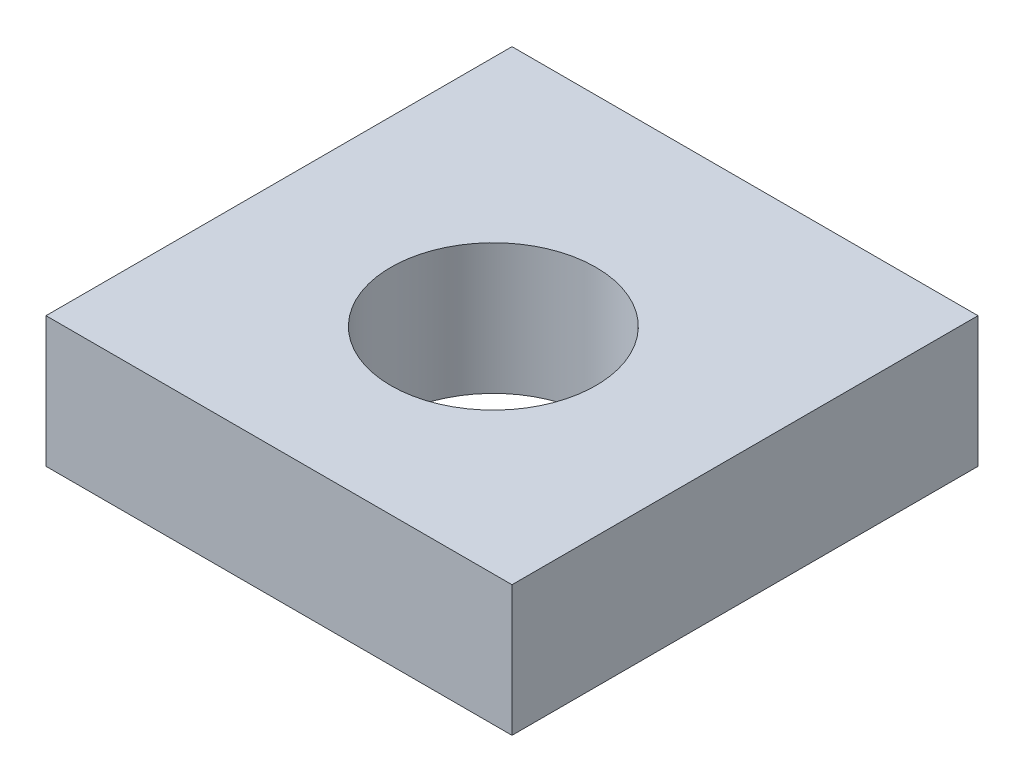
SolidWorks part; units mm, degrees
ref_plane "Front Plane" through (0, 0, 0) normal (0, 0, 1) x (1, 0, 0)
ref_plane "Top Plane" through (0, 0, 0) normal (0, 1, 0) x (1, 0, 0)
ref_plane "Right Plane" through (0, 0, 0) normal (1, 0, 0) x (0, 0, -1)
ref_plane "Plane1" through (0, 478, 0) normal (0, 1, 0) x (1, 0, 0)
sketch "Sketch1" plane through (0, 478, 0) normal (0, 1, 0) x (1, 0, 0)
  line L1 (275, -130) -> (325, -130)
  line L2 (275, -130) -> (275, -180)
  line L3 (275, -180) -> (325, -180)
  line L4 (325, -130) -> (325, -180)
extrude "Boss-Extrude1" add sketch "Sketch1" along normal blind 14
sketch "Sketch2" plane through (0, 492, 0) normal (0, 1, 0) x (1, 0, 0)
  circle A0 centre (300, -157) radius 11
extrude "Cut-Extrude1" cut sketch "Sketch2" against normal blind 34
